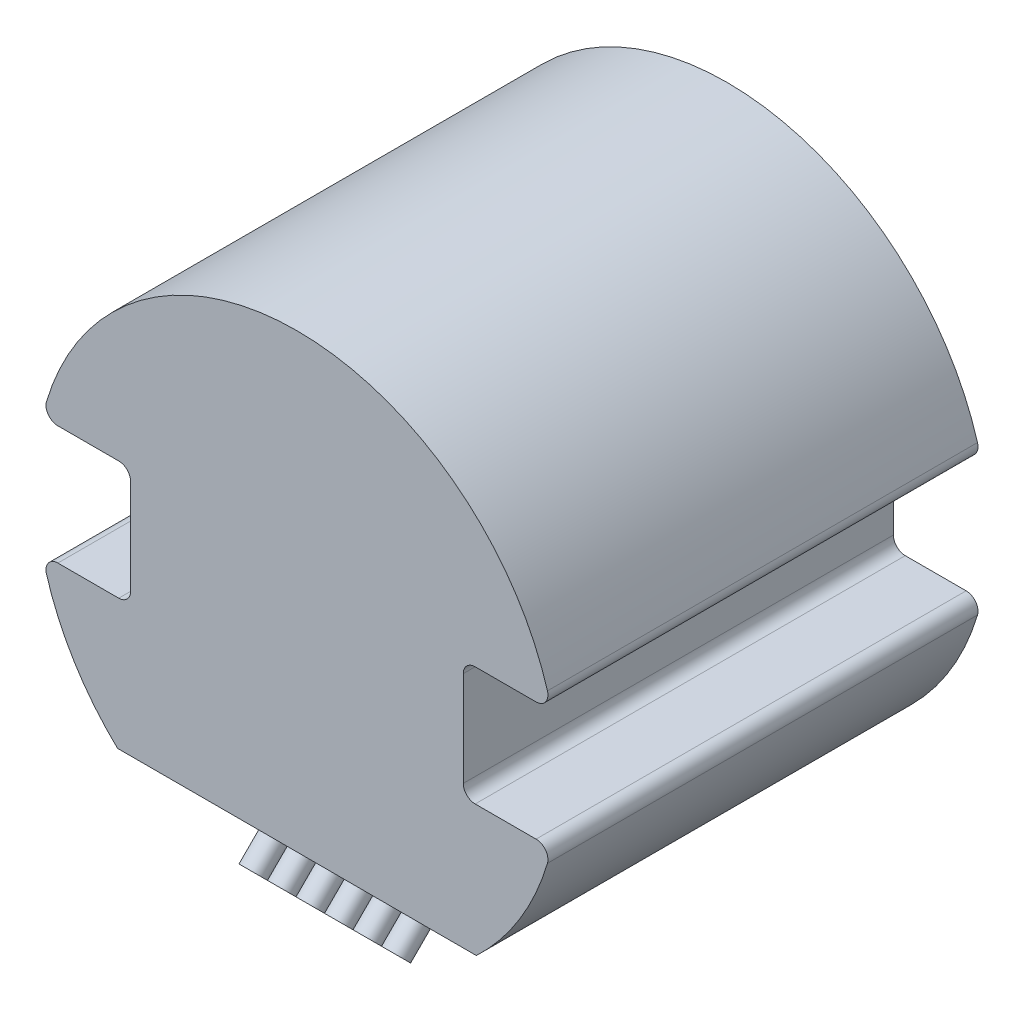
SolidWorks part; units mm, degrees
ref_plane "Plan de face" through (0, 0, 0) normal (0, 0, 1) x (1, 0, 0)
ref_plane "Plan de dessus" through (0, 0, 0) normal (0, 1, 0) x (1, 0, 0)
ref_plane "Plan de droite" through (0, 0, 0) normal (1, 0, 0) x (0, 0, -1)
sketch "Esquisse1" plane through (0, 0, 0) normal (0, 0, 1) x (1, 0, 0)
  circle A0 centre (0, 0) radius 11
  dimension "D1" = 22
extrude "Boss.-Extru.1" add sketch "Esquisse1" along normal blind 18.1
sketch "Esquisse4" plane through (0, 0, 18.1) normal (0, 0, 1) x (1, 0, 0)
  line L0 (0, 0) -> (11, 0) construction
  line L1 (10.7121, 2.5) -> (7, 2.5)
  line L2 (7, 2.5) -> (7, -2.5)
  line L3 (10.7121, -2.5) -> (7, -2.5)
  line L4 (0, 0) -> (0, 3.2039) construction
  line L5 (-10.7121, -2.5) -> (-7, -2.5)
  line L6 (-7, 2.5) -> (-7, -2.5)
  line L7 (-10.7121, 2.5) -> (-7, 2.5)
  circle A0 centre (0, 0) radius 11 construction
  arc A1 (10.7121, -2.5) -> (10.7121, 2.5) centre (0, 0) ccw
  arc A2 (-10.7121, -2.5) -> (-10.7121, 2.5) centre (0, 0) cw
  point P10 (7, 0)
  dimension "D1" = 14
  dimension "D2" = 5
extrude "Enlèv. mat.-Extru.2" cut sketch "Esquisse4" against normal through all
sketch "Esquisse5" plane through (0, 0, 18.1) normal (0, 0, 1) x (1, 0, 0)
  line L0 (-7.5498, -8) -> (7.5498, -8)
  arc A0 (-10.7121, -2.5) -> (10.7121, -2.5) centre (0, 0) ccw construction
  arc A1 (-7.5498, -8) -> (7.5498, -8) centre (0, 0) ccw
  point P5 (0, -11)
  dimension "D1" = 3
extrude "Enlèv. mat.-Extru.3" cut sketch "Esquisse5" against normal blind 4
fillet "Congé1" radius 0.5 8 edges at (10.7121, -2.5, 9.05) (7, -2.5, 9.05) (10.7121, 2.5, 9.05) (7, 2.5, 9.05) (-10.7121, -2.5, 9.05) (-7, -2.5, 9.05) (-7, 2.5, 9.05) (-10.7121, 2.5, 9.05)
ref_plane "Plan1" through (0, -11.05, 11.05) normal (0, -0.7071, 0.7071) x (-1, 0, 0)
sketch "Esquisse6" plane through (0, -11.05, 11.05) normal (0, -0.7071, 0.7071) x (-1, 0, 0)
  line L0 (0, -4.3134) -> (0, -3.4897) construction
  line L1 (-7.5498, -4.3134) -> (7.5498, -4.3134) construction
  line L2 (0.6, -4.3134) -> (-0.6, -4.3134) construction
  line L3 (0.6, -4.3134) -> (1.8, -4.3134) construction
  line L4 (1.8, -4.3134) -> (3, -4.3134) construction
  circle A0 centre (0.6, -4.3134) radius 0.5
  circle A1 centre (1.8, -4.3134) radius 0.5
  circle A2 centre (3, -4.3134) radius 0.5
  circle A3 centre (-3, -4.3134) radius 0.5
  circle A4 centre (-1.8, -4.3134) radius 0.5
  circle A5 centre (-0.6, -4.3134) radius 0.5
  point P12 (0, -4.3134)
  dimension "D1" = 1
  dimension "D2" = 6
extrude "Boss.-Extru.2" add sketch "Esquisse6" along normal blind 4
